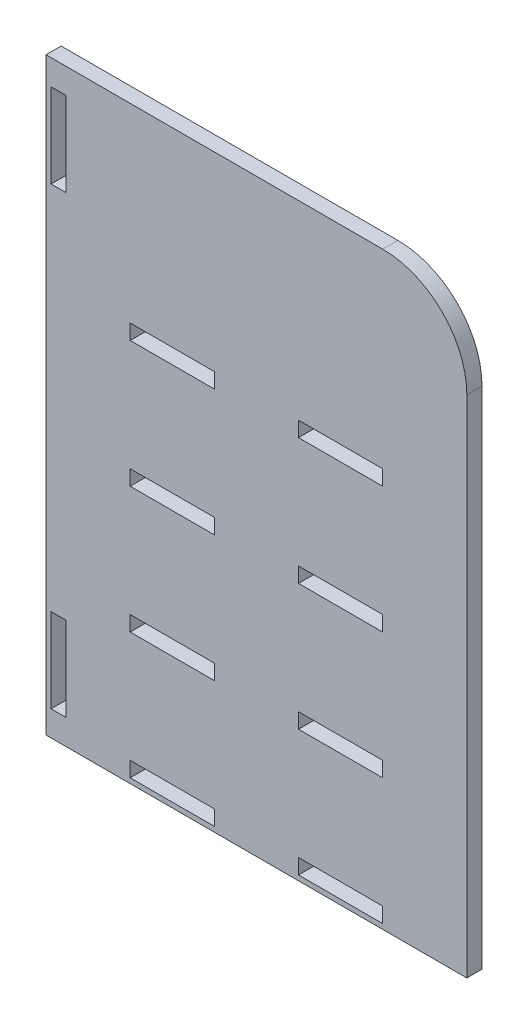
SolidWorks part; units mm, degrees
ref_plane "Front Plane" through (0, 0, 0) normal (0, 0, 1) x (1, 0, 0)
ref_plane "Top Plane" through (0, 0, 0) normal (0, 1, 0) x (1, 0, 0)
ref_plane "Right Plane" through (0, 0, 0) normal (1, 0, 0) x (0, 0, -1)
sketch "Sketch1" plane through (0, 0, 0) normal (0, 0, 1) x (1, 0, 0)
  line L0 (-817.4113, 1115.0159) -> (-990.0864, 1115.0159) construction
  line L1 (-817.4113, 1115.0159) -> (-417.4113, 1115.0159)
  line L2 (-817.4113, 1115.0159) -> (-817.4113, 415.0159)
  line L3 (-817.4113, 415.0159) -> (-317.4113, 415.0159)
  line L4 (-317.4113, 1015.0159) -> (-317.4113, 415.0159)
  line L5 (-817.4113, 1115.0159) -> (-317.4113, 415.0159) construction
  line L6 (-817.4113, 415.0159) -> (-317.4113, 1115.0159) construction
  line L7 (-817.4113, 415.0159) -> (-817.4113, 427.0159) construction
  line L8 (-817.4113, 1115.0159) -> (-990.0864, 1115.0159)
  line L10 (-717.4113, 421.0159) -> (-617.4113, 421.0159)
  line L12 (-517.4113, 571.0159) -> (-517.4113, 589.0159)
  line L13 (-717.4113, 421.0159) -> (-617.4113, 421.0159)
  line L14 (-717.4113, 421.0159) -> (-717.4113, 439.0159)
  line L15 (-717.4113, 439.0159) -> (-617.4113, 439.0159)
  line L16 (-617.4113, 421.0159) -> (-617.4113, 439.0159)
  line L17 (-517.4113, 421.0159) -> (-417.4113, 421.0159)
  line L18 (-517.4113, 421.0159) -> (-517.4113, 439.0159)
  line L19 (-517.4113, 439.0159) -> (-417.4113, 439.0159)
  line L20 (-417.4113, 421.0159) -> (-417.4113, 439.0159)
  line L21 (-517.4113, 571.0159) -> (-417.4113, 571.0159)
  line L22 (-417.4113, 571.0159) -> (-417.4113, 589.0159)
  line L23 (-517.4113, 589.0159) -> (-417.4113, 589.0159)
  line L24 (-717.4113, 571.0159) -> (-717.4113, 589.0159)
  line L25 (-717.4113, 571.0159) -> (-617.4113, 571.0159)
  line L26 (-617.4113, 571.0159) -> (-617.4113, 589.0159)
  line L27 (-717.4113, 589.0159) -> (-617.4113, 589.0159)
  line L28 (-517.4113, 721.0159) -> (-517.4113, 739.0159)
  line L29 (-517.4113, 721.0159) -> (-417.4113, 721.0159)
  line L30 (-417.4113, 721.0159) -> (-417.4113, 739.0159)
  line L31 (-517.4113, 739.0159) -> (-417.4113, 739.0159)
  line L32 (-717.4113, 721.0159) -> (-717.4113, 739.0159)
  line L33 (-717.4113, 721.0159) -> (-617.4113, 721.0159)
  line L34 (-617.4113, 721.0159) -> (-617.4113, 739.0159)
  line L35 (-717.4113, 739.0159) -> (-617.4113, 739.0159)
  line L36 (-517.4113, 871.0159) -> (-517.4113, 889.0159)
  line L37 (-517.4113, 871.0159) -> (-417.4113, 871.0159)
  line L38 (-417.4113, 871.0159) -> (-417.4113, 889.0159)
  line L39 (-517.4113, 889.0159) -> (-417.4113, 889.0159)
  line L40 (-717.4113, 871.0159) -> (-717.4113, 889.0159)
  line L41 (-717.4113, 871.0159) -> (-617.4113, 871.0159)
  line L42 (-617.4113, 871.0159) -> (-617.4113, 889.0159)
  line L43 (-717.4113, 889.0159) -> (-617.4113, 889.0159)
  line L44 (-817.4113, 765.0159) -> (-735.1536, 765.0159) construction
  line L45 (-811.4113, 545.0159) -> (-793.4113, 545.0159)
  line L46 (-817.4113, 1085.0159) -> (-811.4113, 1085.0159)
  line L47 (-793.4113, 445.0159) -> (-793.4113, 545.0159)
  line L48 (-811.4113, 1085.0159) -> (-793.4113, 1085.0159)
  line L49 (-811.4113, 1085.0159) -> (-811.4113, 985.0159)
  line L50 (-811.4113, 985.0159) -> (-793.4113, 985.0159)
  line L51 (-793.4113, 1085.0159) -> (-793.4113, 985.0159)
  line L52 (-811.4113, 445.0159) -> (-793.4113, 445.0159)
  line L53 (-811.4113, 445.0159) -> (-811.4113, 545.0159)
  arc A0 (-317.4113, 1015.0159) -> (-417.4113, 1115.0159) centre (-417.4113, 1015.0159) ccw
  point P0 (-567.4113, 765.0159)
  dimension "D5" = 100
  dimension "D1" = 700
  dimension "D2" = 4
  dimension "D3" = 700
  dimension "D4" = 500
  dimension "D6" = 100
  dimension "D7" = 200
  dimension "D8" = 18
  dimension "D9" = 100
  dimension "D10" = 18
  dimension "D11" = 100
  dimension "D12" = 6
  dimension "D13" = 18
  dimension "D14" = 6
extrude "Boss-Extrude1" add sketch "Sketch1" along normal blind 18
